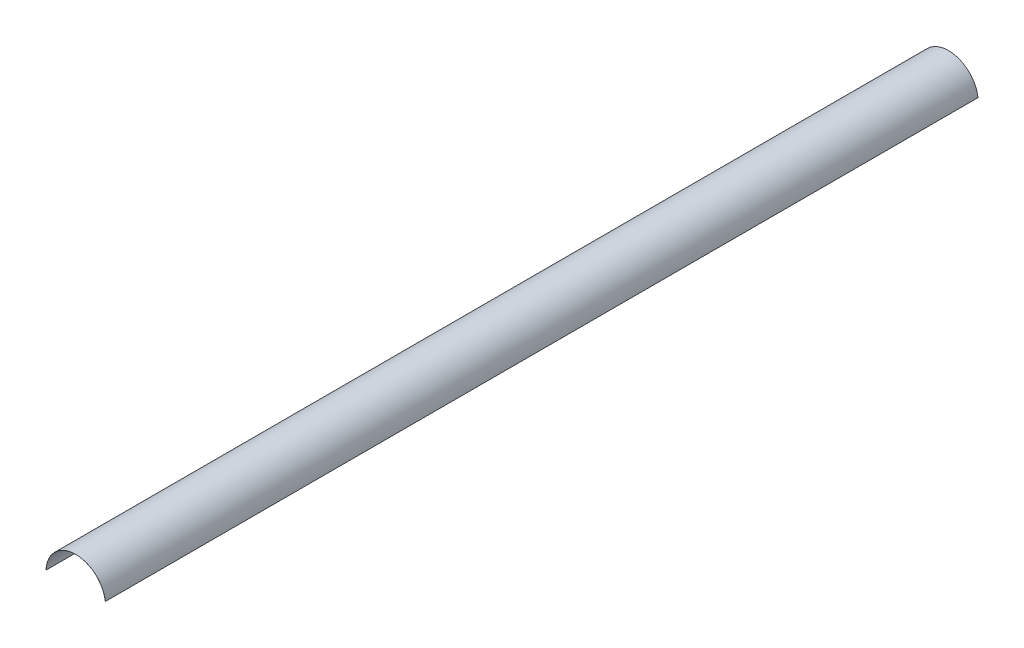
SolidWorks part; units mm, degrees
ref_plane "Front Plane" through (0, 0, 0) normal (0, 0, 1) x (1, 0, 0)
ref_plane "Top Plane" through (0, 0, 0) normal (0, 1, 0) x (1, 0, 0)
ref_plane "Right Plane" through (0, 0, 0) normal (1, 0, 0) x (0, 0, -1)
sketch "Sketch1" plane through (0, 0, 0) normal (0, 0, 1) x (1, 0, 0)
  arc A0 (0, 0) -> (207.2116, 8.6895) centre (103.9716, -4.3791) cw
extrude "Extrude-Thin1" add sketch "Sketch1" along normal blind 3048 thin
